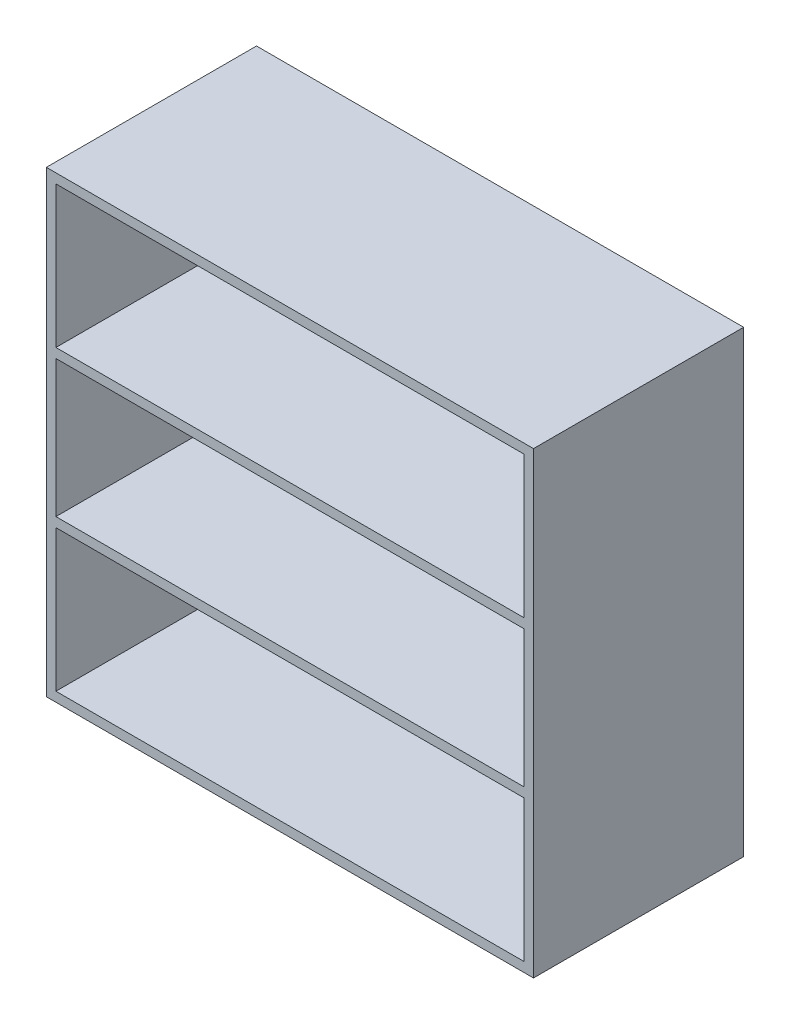
SolidWorks part; units mm, degrees
ref_plane "Front" through (0, 0, 0) normal (0, 0, 1) x (1, 0, 0)
ref_plane "Top" through (0, 0, 0) normal (0, 1, 0) x (1, 0, 0)
ref_plane "Right" through (0, 0, 0) normal (1, 0, 0) x (0, 0, -1)
sketch "Sketch1" plane through (0, 0, 0) normal (0, 1, 0) x (1, 0, 0)
  line L1 (-1295.4, 558.8) -> (1295.4, 558.8)
  line L2 (-1295.4, 558.8) -> (-1295.4, -558.8)
  line L3 (-1295.4, -558.8) -> (1295.4, -558.8)
  line L4 (1295.4, 558.8) -> (1295.4, -558.8)
  line L5 (-1295.4, 558.8) -> (1295.4, -558.8) construction
  line L6 (-1295.4, -558.8) -> (1295.4, 558.8) construction
  point P0 (0, 0)
  dimension "D1" = 2590.8
  dimension "D2" = 1117.6
extrude "Boss-Extrude1" add sketch "Sketch1" along normal blind 2438.4
sketch "Sketch2" plane through (0, 0, 558.8) normal (0, 0, 1) x (1, 0, 0)
  line L0 (-1244.6, 50.8) -> (1244.6, 50.8)
  line L1 (1244.6, 50.8) -> (1244.6, 804.3333)
  line L2 (1244.6, 2387.6) -> (-1244.6, 2387.6)
  line L3 (-1244.6, 2387.6) -> (-1244.6, 1634.0667)
  line L4 (-1295.4, 0) -> (1295.4, 0)
  line L5 (1295.4, 0) -> (1295.4, 2438.4)
  line L6 (1295.4, 2438.4) -> (-1295.4, 2438.4)
  line L7 (-1295.4, 2438.4) -> (-1295.4, 0)
  line L8 (-1295.4, 0) -> (1295.4, 0) construction
  line L9 (1295.4, 0) -> (1295.4, 2438.4) construction
  line L10 (1295.4, 2438.4) -> (-1295.4, 2438.4) construction
  line L11 (-1295.4, 2438.4) -> (-1295.4, 0) construction
  line L12 (-1244.6, 1608.6667) -> (1244.6, 1608.6667) construction
  line L13 (-1244.6, 829.7333) -> (1244.6, 829.7333) construction
  line L14 (0, 1608.6667) -> (0, 2387.6) construction
  line L15 (0, 1608.6667) -> (0, 829.7333) construction
  line L16 (0, 829.7333) -> (0, 50.8) construction
  line L17 (-1244.6, 1583.2667) -> (1244.6, 1583.2667)
  line L18 (-1244.6, 804.3333) -> (1244.6, 804.3333)
  line L19 (-1244.6, 1634.0667) -> (1244.6, 1634.0667)
  line L20 (-1244.6, 855.1333) -> (1244.6, 855.1333)
  line L21 (-1244.6, 1583.2667) -> (-1244.6, 855.1333)
  line L22 (-1244.6, 2387.6) -> (-1244.6, 50.8) construction
  line L23 (-1244.6, 804.3333) -> (-1244.6, 50.8)
  line L24 (1244.6, 855.1333) -> (1244.6, 1583.2667)
  line L25 (1244.6, 50.8) -> (1244.6, 2387.6) construction
  line L26 (1244.6, 1634.0667) -> (1244.6, 2387.6)
  dimension "D1" = 0
  dimension "D2" = 50.8
  dimension "D3" = 25.4
  dimension "D4" = 25.4
extrude "Cut-Extrude1" cut sketch "Sketch2" against normal through all
